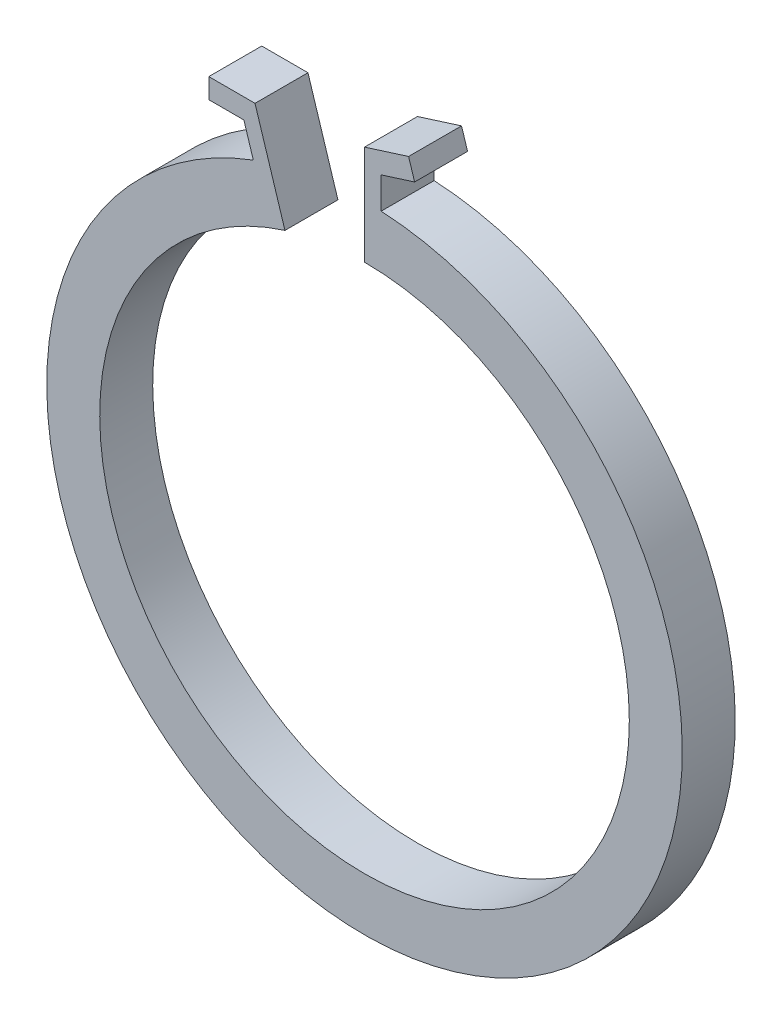
SolidWorks part; units mm, degrees
ref_plane "前视基准面" through (0, 0, 0) normal (0, 0, 1) x (1, 0, 0)
ref_plane "上视基准面" through (0, 0, 0) normal (0, 1, 0) x (1, 0, 0)
ref_plane "右视基准面" through (0, 0, 0) normal (1, 0, 0) x (0, 0, -1)
sketch "草图1" plane through (0, 0, 0) normal (0, 0, 1) x (1, 0, 0)
  circle A0 centre (0, 0) radius 5
  circle A1 centre (0, 0) radius 6
  dimension "D1" = 10
  dimension "D2" = 12
extrude "凸台-拉伸1" add sketch "草图1" along normal blind 1
sketch "草图2" plane through (0, 0, 1) normal (0, 0, 1) x (1, 0, 0)
  line L0 (0, 0) -> (0, 9.5521)
  line L1 (0, 9.5521) -> (-2.7972, 8.8801)
  line L2 (-2.7972, 8.8801) -> (0, 0)
extrude "切除-拉伸1" cut sketch "草图2" against normal blind 1
sketch "草图3" plane through (0, 0, 1) normal (0, 0, 1) x (1, 0, 0)
  line L1 (0, 6) -> (0, 6.8829)
  line L2 (0, 6.8829) -> (0.832, 7.1459)
  line L3 (0.832, 7.1459) -> (0.946, 6.7853)
  line L4 (0.946, 6.7853) -> (0.314, 6.5855)
  line L5 (0.314, 6.5855) -> (0.314, 5.9918)
  line L6 (0.314, 5.9918) -> (0, 6)
  line L7 (-1.5022, 4.769) -> (0, 5) construction
  line L8 (0, 0) -> (-0.7511, 4.8845) construction
  line L9 (-2.0997, 5.6206) -> (-1.8027, 5.7228)
  line L10 (-2.2781, 6.1869) -> (-2.0997, 5.6206)
  line L11 (-2.9408, 6.1876) -> (-2.2781, 6.1869)
  line L12 (-2.9405, 6.5658) -> (-2.9408, 6.1876)
  line L13 (-2.0679, 6.5649) -> (-2.9405, 6.5658)
  line L14 (-1.8027, 5.7228) -> (-2.0679, 6.5649)
  arc A2 (-1.8027, 5.7228) -> (0, 6) centre (0, 0) ccw construction
extrude "凸台-拉伸2" add sketch "草图3" against normal blind 1
